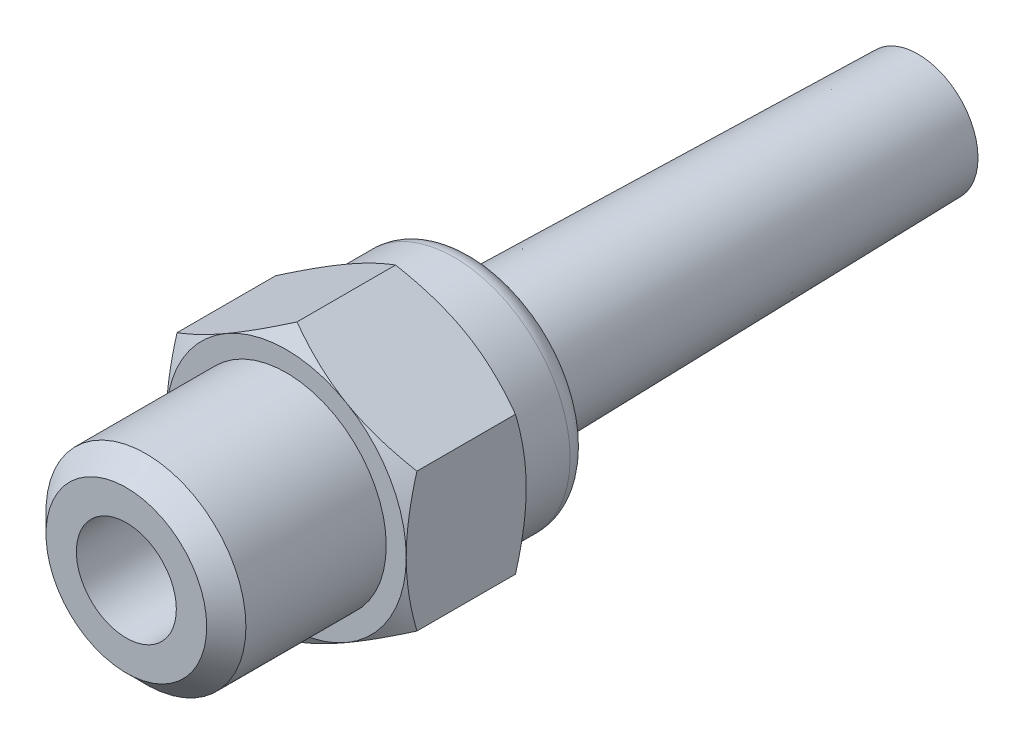
SolidWorks part; units mm, degrees
ref_plane "Front Plane" through (0, 0, 0) normal (0, 0, 1) x (1, 0, 0)
ref_plane "Top Plane" through (0, 0, 0) normal (0, 1, 0) x (1, 0, 0)
ref_plane "Right Plane" through (0, 0, 0) normal (1, 0, 0) x (0, 0, -1)
ref_plane "Plane1" through (0, 0, 0) normal (1, 0, 0) x (0, 0, -1)
sketch "Sketch1" plane through (0, 0, 0) normal (1, 0, 0) x (0, 0, -1)
  line L0 (4, 0) -> (4, 1.25)
  line L1 (4, 1.25) -> (0, 1.25)
  line L2 (0, 1.25) -> (0, 2.0095)
  line L3 (0, 2.0095) -> (0.4905, 2.5)
  line L4 (0.4905, 2.5) -> (4, 2.5)
  line L5 (4, 2.5) -> (4, 3)
  line L6 (4, 3) -> (4.3464, 3.6)
  line L7 (4.3464, 3.6) -> (6.6536, 3.6)
  line L8 (6.6536, 3.6) -> (7, 3)
  line L9 (7, 3) -> (7, 2.9)
  line L10 (7, 2.9) -> (8.2, 2.9)
  line L11 (8.7, 2.4) -> (8.7, 1.7415)
  line L12 (8.7, 1.7415) -> (19.8, 1.5)
  line L13 (19.8, 1.5) -> (19.8, 0)
  line L14 (19.8, 0) -> (4, 0)
  line L15 (19.8, 0) -> (0, 0) construction
  arc A0 (8.2, 2.9) -> (8.7, 2.4) centre (8.2, 2.4) cw
revolve "Revolve1" add sketch "Sketch1" angle 360 about L15
cosmetic thread "Cosmetic Thread1" parameters "D1"=4, "D2"=4.019
ref_plane "Plane2" through (0, 0, -4) normal (0, 0, 1) x (1, 0, 0)
sketch "Sketch2" plane through (0, 0, -4) normal (0, 0, 1) x (1, 0, 0)
  line L0 (-6, 6) -> (-6, -6)
  line L1 (-6, -6) -> (6, -6)
  line L2 (6, -6) -> (6, 6)
  line L3 (6, 6) -> (-6, 6)
  line L4 (-3, -1.7321) -> (0, -3.4641)
  line L5 (0, -3.4641) -> (3, -1.7321)
  line L6 (3, -1.7321) -> (3, 1.7321)
  line L7 (3, 1.7321) -> (0, 3.4641)
  line L8 (0, 3.4641) -> (-3, 1.7321)
  line L9 (-3, 1.7321) -> (-3, -1.7321)
extrude "Cut-Extrude1" cut sketch "Sketch2" against normal blind 3
